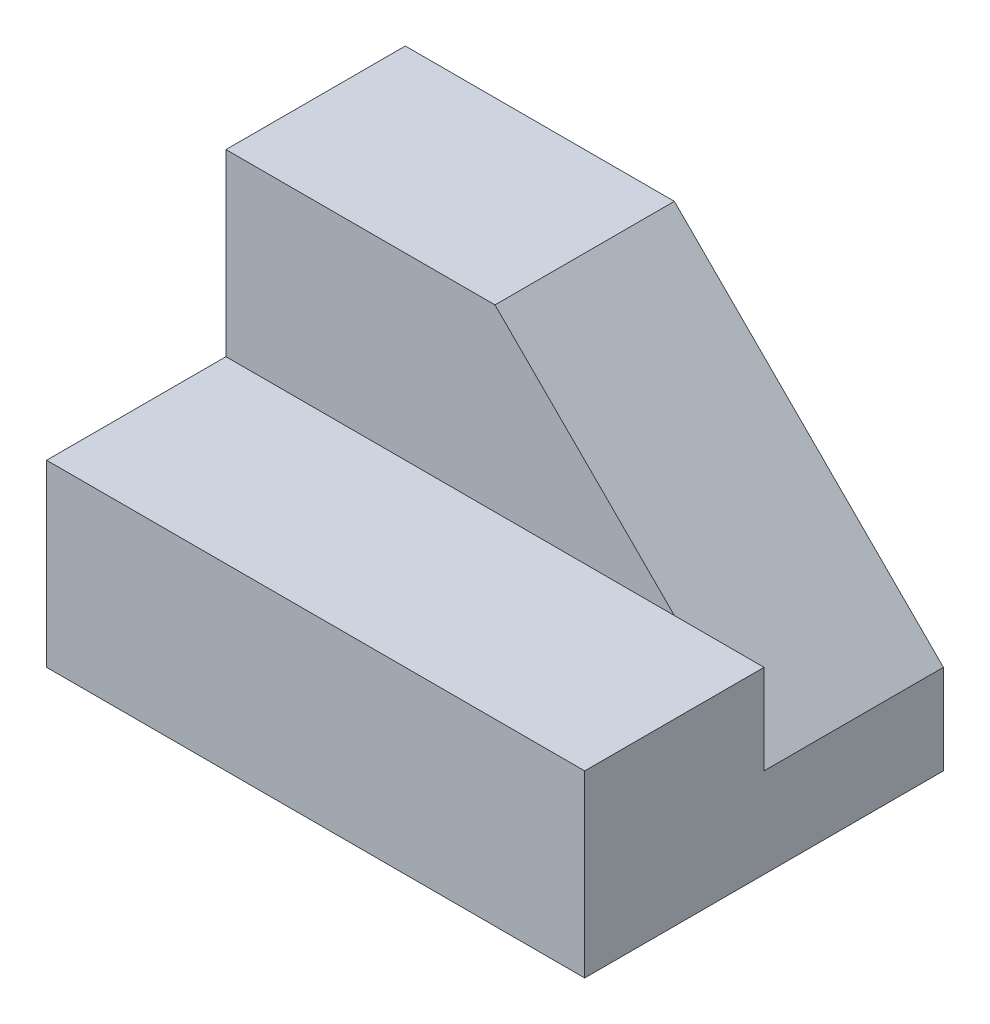
SolidWorks part; units mm, degrees
ref_plane "前基準面" through (0, 0, 0) normal (0, 0, 1) x (1, 0, 0)
ref_plane "上基準面" through (0, 0, 0) normal (0, 1, 0) x (1, 0, 0)
ref_plane "右基準面" through (0, 0, 0) normal (1, 0, 0) x (0, 0, -1)
sketch "草圖1" plane through (0, 0, 0) normal (0, 1, 0) x (1, 0, 0)
  line L1 (0, 0) -> (30, 0)
  line L2 (0, 0) -> (0, 10)
  line L3 (0, 10) -> (30, 10)
  line L4 (30, 0) -> (30, 10)
  dimension "D1" = 30
  dimension "D2" = 10
extrude "填料-伸長1" add sketch "草圖1" along normal blind 10
sketch "草圖2" plane through (0, 0, -10) normal (0, 0, -1) x (-1, 0, 0)
  line L0 (0, 5) -> (0, 20)
  line L1 (0, 10) -> (0, 0) construction
  line L2 (0, 20) -> (-15, 20)
  line L3 (-15, 20) -> (-30, 5)
  line L4 (-30, 10) -> (-30, 0) construction
  line L5 (-30, 5) -> (0, 5)
  line L6 (-30, 10) -> (0, 10) construction
  dimension "D1" = 5
  dimension "D2" = 15
  dimension "D3" = 15
extrude "填料-伸長2" add sketch "草圖2" along normal blind 10
sketch "草圖3" plane through (0, 0, -10) normal (0, 0, -1) x (-1, 0, 0)
  line L4 (0, 5) -> (-30, 5)
  line L5 (-30, 5) -> (-30, 0)
  line L6 (-30, 0) -> (0, 0)
  line L7 (0, 0) -> (0, 5)
  line L8 (0, 5) -> (-30, 5)
  line L9 (-30, 5) -> (-30, 0)
  line L10 (-30, 0) -> (0, 0)
  line L11 (0, 0) -> (0, 5)
  dimension "D1" = 0
extrude "填料-伸長3" add sketch "草圖3" along normal up to vertex (10 mm away) up to point (30, 5, -20)
